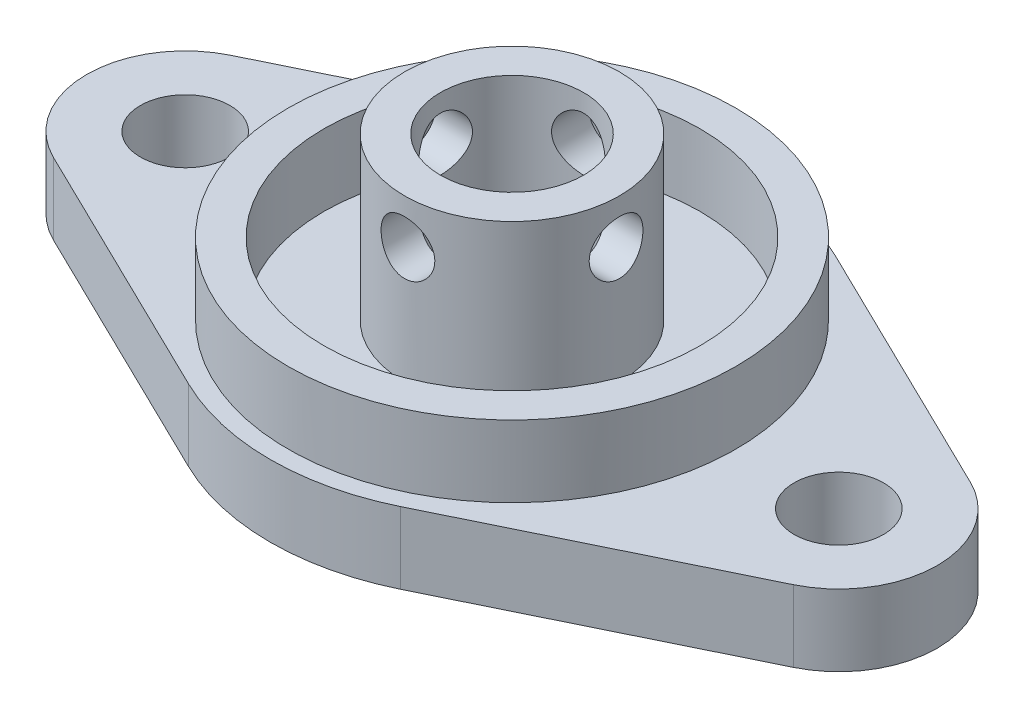
SolidWorks part; units mm, degrees
ref_plane "Front Plane" through (0, 0, 0) normal (0, 0, 1) x (1, 0, 0)
ref_plane "Top Plane" through (0, 0, 0) normal (0, 1, 0) x (1, 0, 0)
ref_plane "Right Plane" through (0, 0, 0) normal (1, 0, 0) x (0, 0, -1)
sketch "Sketch1" plane through (0, 0, 0) normal (0, 1, 0) x (1, 0, 0)
  line L0 (0, 13.5) -> (0, -13.5) construction
  line L1 (-13.5, 0) -> (13.5, 0) construction
  line L2 (20.661, 4.9434) -> (5.9178, 12.1338)
  line L3 (20.661, -4.9434) -> (5.9178, -12.1338)
  line L4 (-20.661, -4.9434) -> (-5.9178, -12.1338)
  line L5 (-20.661, 4.9434) -> (-5.9178, 12.1338)
  arc A0 (-5.9178, -12.1338) -> (5.9178, -12.1338) centre (0, 0) ccw
  circle A1 centre (18.25, 0) radius 2.5
  arc A2 (20.661, 4.9434) -> (20.661, -4.9434) centre (18.25, 0) cw
  arc A3 (-20.661, 4.9434) -> (-20.661, -4.9434) centre (-18.25, 0) ccw
  circle A4 centre (-18.25, 0) radius 2.5
  arc A5 (5.9178, 12.1338) -> (-5.9178, 12.1338) centre (0, 0) ccw
  point P6 (0, 0)
  point P9 (0, 0)
  point P13 (0, 0)
  point P15 (5.9225, 12.1315)
  point P16 (0, 0)
  dimension "D1" = 27
  dimension "D2" = 5
  dimension "D4" = 5.5
  dimension "D3" = 36.5
extrude "Boss-Extrude1" add sketch "Sketch1" along normal blind 4
sketch "Sketch2" plane through (0, 4, 0) normal (0, 1, 0) x (1, 0, 0)
  circle A0 centre (0, 0) radius 12.5
  dimension "D1" = 25
extrude "Extrude-Thin1" add sketch "Sketch2" along normal blind 4 thin thin type one direction reverse wall 2
sketch "Sketch3" plane through (0, 4, 0) normal (0, 1, 0) x (1, 0, 0)
  circle A0 centre (0, 0) radius 4
  dimension "D1" = 8
extrude "Extrude-Thin2" add sketch "Sketch3" along normal blind 9 thin
sketch "Sketch4" plane through (0, 0, 0) normal (0, 0, 1) x (1, 0, 0)
  line L4 (-1.5, 10.5) -> (1.5, 10.5) construction
  line L5 (4, 13) -> (-4, 13) construction
  line L6 (12.5, 8) -> (-12.5, 8) construction
  circle A0 centre (0, 10.5) radius 1.5
  dimension "D1" = 3
extrude "Cut-Extrude1" cut sketch "Sketch4" against normal through all both and the other way through all
pattern_circular "CirPattern1" count 2 over 90 about axis through (0, 13, 0) along (0, 1, 0) of "Cut-Extrude1"
